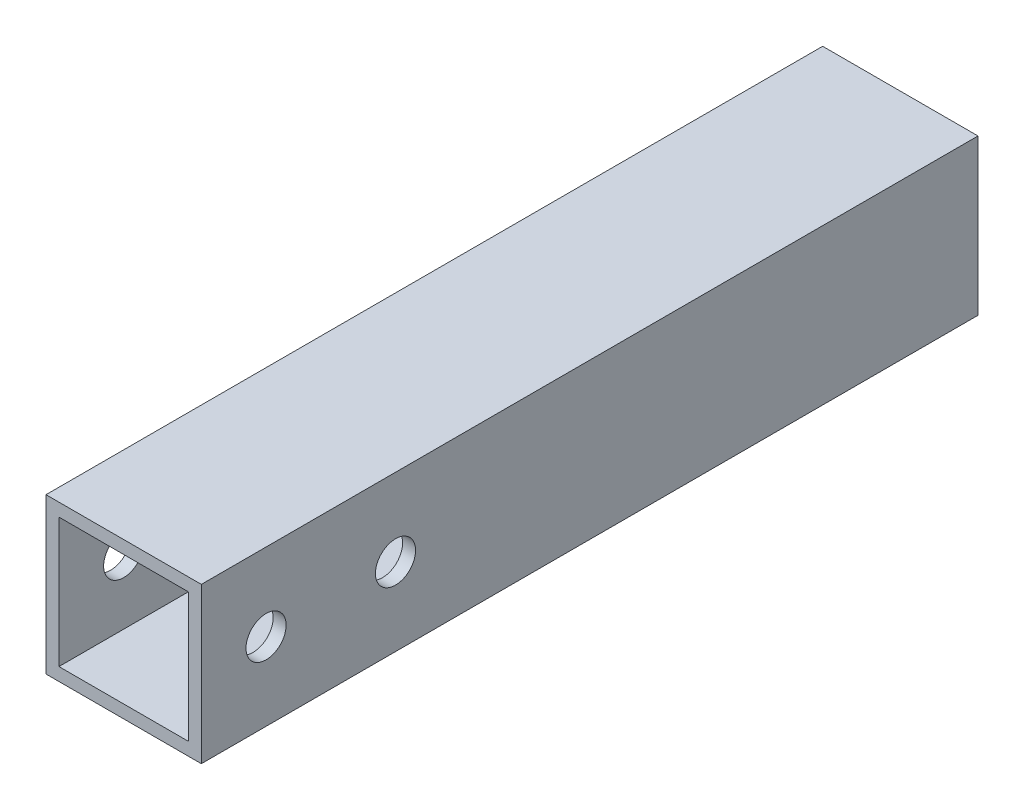
SolidWorks part; units mm, degrees
material "Thornel Mat VMA"
ref_plane "前视基准面" through (0, 0, 0) normal (0, 0, 1) x (1, 0, 0)
ref_plane "上视基准面" through (0, 0, 0) normal (0, 1, 0) x (1, 0, 0)
ref_plane "右视基准面" through (0, 0, 0) normal (1, 0, 0) x (0, 0, -1)
other "Configuration Table"
sketch "草图1" plane through (0, 0, 0) normal (0, 0, 1) x (1, 0, 0)
  line L0 (1, 1) -> (1, 11)
  line L1 (0, 0) -> (12, 0)
  line L2 (0, 0) -> (0, 12)
  line L3 (0, 12) -> (12, 12)
  line L4 (12, 0) -> (12, 12)
  line L5 (1, 11) -> (11, 11)
  line L6 (11, 1) -> (11, 11)
  line L7 (1, 1) -> (11, 1)
  dimension "D1" = 12
  dimension "D2" = 12
  dimension "D3" = 1
extrude "凸台-拉伸1" add sketch "草图1" along normal blind 60
sketch "草图2" plane through (12, 0, 0) normal (1, 0, 0) x (0, 1, 0)
  line L0 (6, 60) -> (6, 0) construction
  line L1 (0, 60) -> (12, 60) construction
  line L2 (0, 0) -> (12, 0) construction
  circle A0 centre (6, 45) radius 1.55
  circle A1 centre (6, 55) radius 1.55
  point P10 (6, 48.5043)
  point P11 (6, 55.2278)
  dimension "D1" = 3.1
  dimension "D2" = 3.1
  dimension "D3" = 5
  dimension "D4" = 10
extrude "切除-拉伸2" cut sketch "草图2" against normal through all
